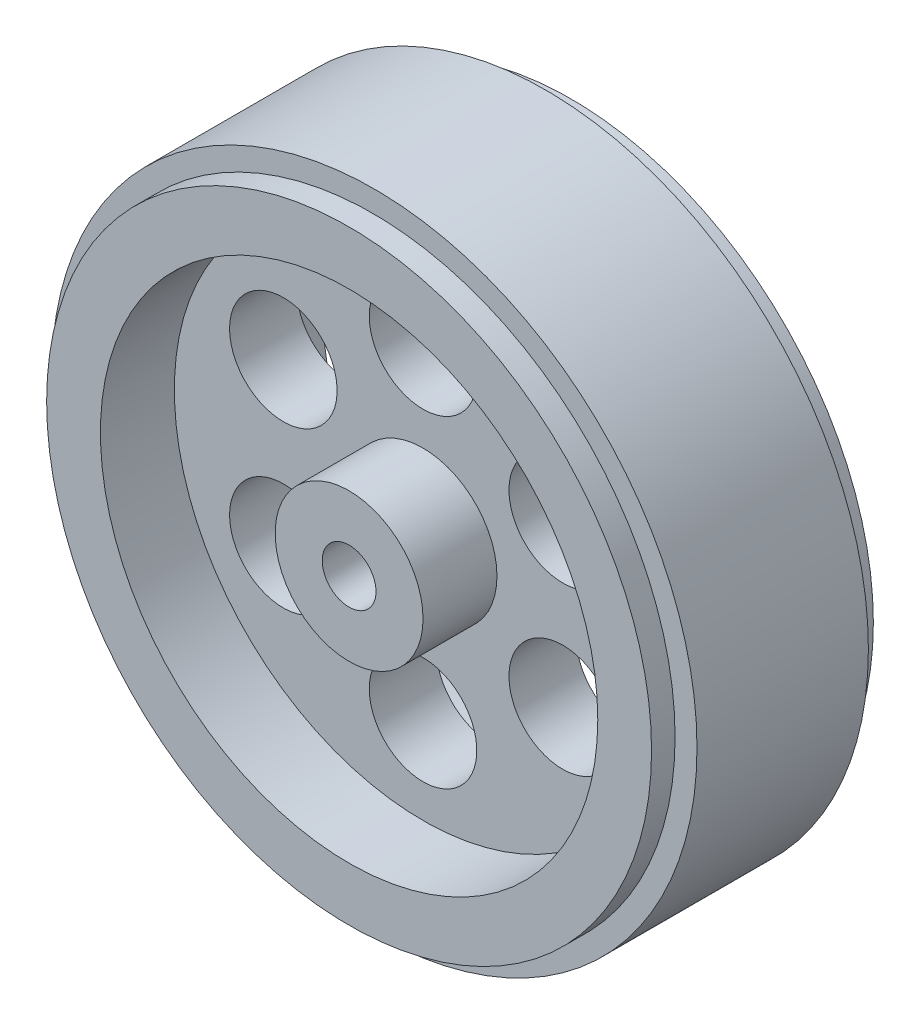
SolidWorks part; units mm, degrees
ref_plane "Front Plane" through (0, 0, 0) normal (0, 0, 1) x (1, 0, 0)
ref_plane "Top Plane" through (0, 0, 0) normal (0, 1, 0) x (1, 0, 0)
ref_plane "Right Plane" through (0, 0, 0) normal (1, 0, 0) x (0, 0, -1)
sketch "Sketch1" plane through (0, 0, 0) normal (1, 0, 0) x (0, 0, -1)
  line L0 (0, 69.4943) -> (0, -76.1525) construction
  line L1 (-177.273, 0) -> (0, 0) construction
  line L2 (13, 42) -> (-13, 42)
  line L3 (-13, 42) -> (-13, 45)
  line L4 (-13, 45) -> (-16.5, 45)
  line L5 (-16.5, 45) -> (-16.5, 37)
  line L9 (4.5, 37) -> (4.5, 4)
  line L10 (16.5, 37) -> (4.5, 37)
  line L11 (16.5, 45) -> (16.5, 37)
  line L12 (13, 45) -> (16.5, 45)
  line L13 (13, 42) -> (13, 45)
  line L14 (12.75, 42.01) -> (12.75, 48.01)
  line L15 (12.75, 48.01) -> (-12.75, 48.01)
  line L16 (12.75, 42.01) -> (-12.75, 42.01)
  line L17 (-12.75, 42.01) -> (-12.75, 48.01)
  line L18 (4.5, 4) -> (-16.5, 4)
  line L19 (-16.5, 4) -> (-16.5, 11)
  line L20 (-16.5, 11) -> (-5.5, 11)
  line L22 (-5.5, 11) -> (-5.5, 37)
  line L23 (-5.5, 37) -> (-16.5, 37)
  point P14 (0, 4)
  point P19 (0, 42)
  point P24 (0, 42.01)
  point P25 (0, 48.01)
  dimension "D1" = 42
  dimension "D2" = 45
  dimension "D3" = 4
  dimension "D4" = 13
  dimension "D5" = 16.5
  dimension "D7" = 10
  dimension "D8" = 0.25
  dimension "D9" = 0.01
  dimension "D10" = 6
  dimension "D11" = 12
  dimension "D12" = 11
  dimension "D13" = 3.5
  dimension "D14" = 3.5
  dimension "D15" = 5
revolve "Revolve1" add sketch "Sketch1" angle 360 about L1
sketch "Sketch2" plane through (0, 0, -4.5) normal (0, 0, -1) x (-1, 0, 0)
  circle A1 centre (0, 24) radius 8
  circle A2 centre (20.7846, 12) radius 8
  circle A3 centre (20.7846, -12) radius 8
  circle A4 centre (0, -24) radius 8
  circle A5 centre (-20.7846, -12) radius 8
  circle A6 centre (-20.7846, 12) radius 8
  point P17 (0, 0)
  dimension "D1" = 24
  dimension "D2" = 16
  dimension "D4" = 6
extrude "Cut-Extrude1" cut sketch "Sketch2" against normal through all
